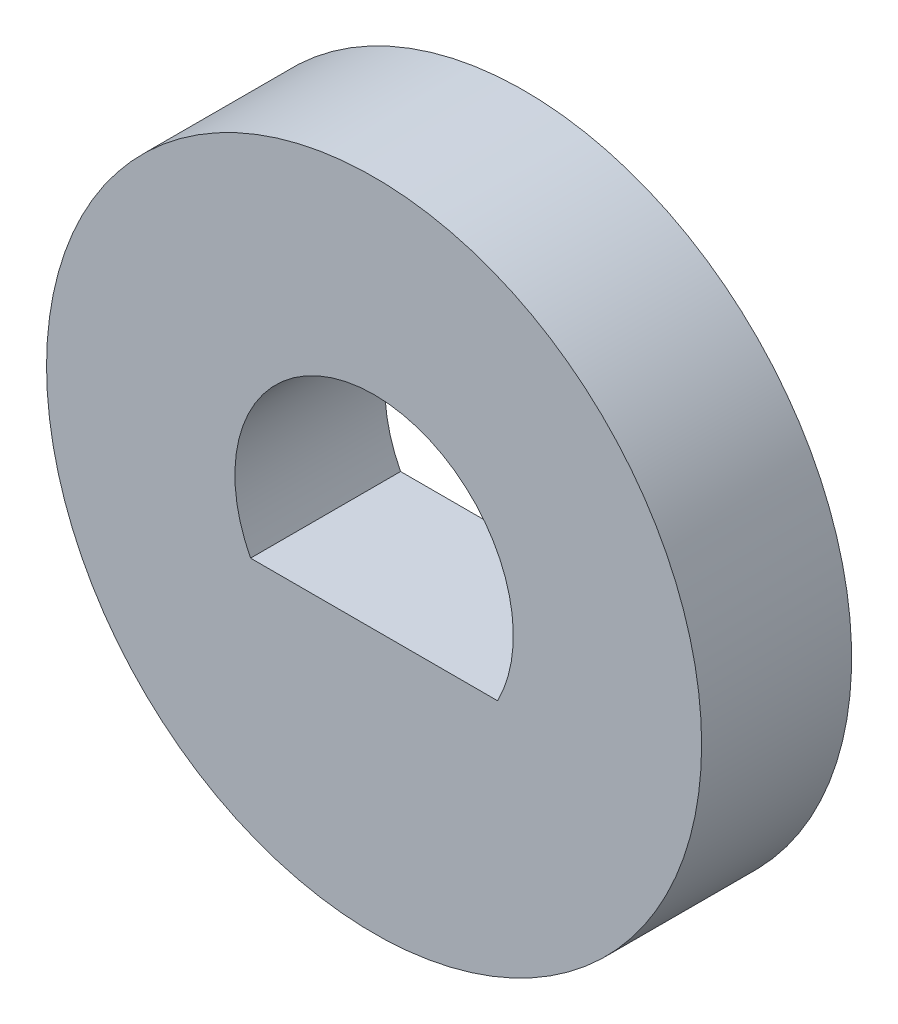
SolidWorks part; units mm, degrees
ref_plane "Front Plane" through (0, 0, 0) normal (0, 0, 1) x (1, 0, 0)
ref_plane "Top Plane" through (0, 0, 0) normal (0, 1, 0) x (1, 0, 0)
ref_plane "Right Plane" through (0, 0, 0) normal (1, 0, 0) x (0, 0, -1)
sketch "Sketch1" plane through (0, 0, -27.4331) normal (0, 0, -1) x (-1, 0, 0)
  line L0 (-1.8855, -0.98) -> (1.8855, -0.98)
  line L1 (-1.862, -0.73) -> (1.862, -0.73) construction
  arc A0 (1.8855, -0.98) -> (-1.8855, -0.98) centre (0, 0) ccw
  circle A2 centre (0, 0) radius 2 construction
  circle A3 centre (0, 0) radius 5
  dimension "D1" = 0.125
  dimension "D3" = 10
  dimension "D2" = 0.25
extrude "Boss-Extrude1" add sketch "Sketch1" against normal offset from surface (2.29 mm away) 0.25
sketch "Sketch2" plane through (0, 0, -27.4331) normal (0, 0, -1) x (-1, 0, 0)
  circle A0 centre (0, 0) radius 5
